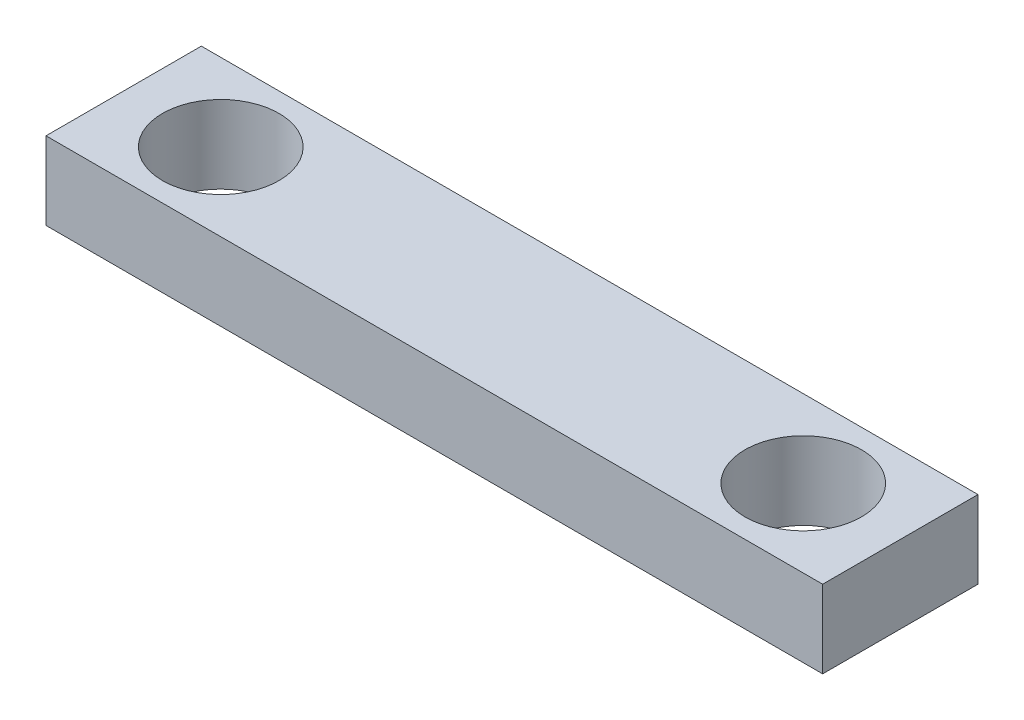
SolidWorks part; units mm, degrees
ref_plane "前视基准面" through (0, 0, 0) normal (0, 0, 1) x (1, 0, 0)
ref_plane "上视基准面" through (0, 0, 0) normal (0, 1, 0) x (1, 0, 0)
ref_plane "右视基准面" through (0, 0, 0) normal (1, 0, 0) x (0, 0, -1)
sketch "草图1" plane through (0, 0, 0) normal (0, 1, 0) x (1, 0, 0)
  line L0 (-10, 0) -> (10, 0) construction
  line L1 (-10, -2) -> (10, -2)
  line L2 (-10, -2) -> (-10, 2)
  line L3 (-10, 2) -> (10, 2)
  line L4 (10, -2) -> (10, 2)
  line L5 (-10, -2) -> (10, 2) construction
  line L6 (-10, 2) -> (10, -2) construction
  circle A0 centre (-7.5, 0) radius 1.5
  circle A1 centre (7.5, 0) radius 1.5
  point P0 (0, 0)
  point P14 (-7.7806, -0.6521)
  dimension "D2" = 3
  dimension "D3" = 3
  dimension "D1" = 15
  dimension "D4" = 20
  dimension "D5" = 4
  dimension "D6" = 2.5
extrude "凸台-拉伸1" add sketch "草图1" along normal blind 2
